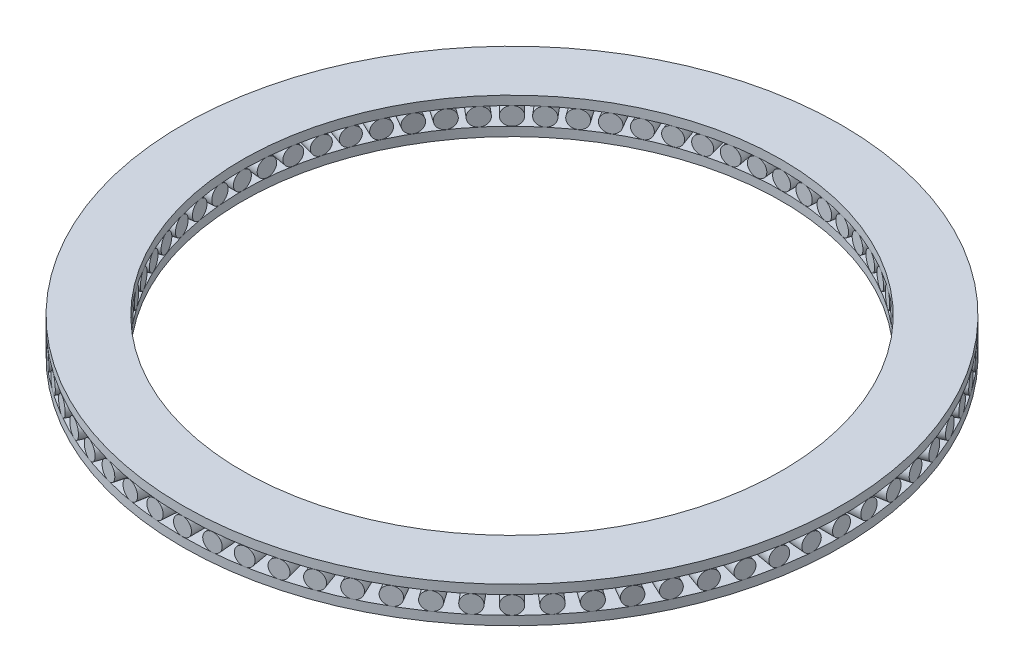
SolidWorks part; units mm, degrees
ref_plane "前视基准面" through (0, 0, 0) normal (0, 0, 1) x (1, 0, 0)
ref_plane "上视基准面" through (0, 0, 0) normal (0, 1, 0) x (1, 0, 0)
ref_plane "右视基准面" through (0, 0, 0) normal (1, 0, 0) x (0, 0, -1)
sketch "草图1" plane through (0, 0, 0) normal (0, 1, 0) x (1, 0, 0)
  circle A0 centre (0, 0) radius 55
  circle A1 centre (0, 0) radius 45
  dimension "D1" = 110
  dimension "D2" = 90
extrude "凸台-拉伸1" add sketch "草图1" along normal blind 1.5
sketch "草图2" plane through (0, 0, 0) normal (0, 0, 1) x (1, 0, 0)
  circle A0 centre (0, 3) radius 1.5
extrude "凸台-拉伸2" add sketch "草图2" along normal blind 10 from offset 45 separate body
pattern_circular "阵列(圆周)3" count 72 over 360 about axis through (0, 0, 0) along (0, 1, 0)
sketch "草图3" plane through (0, 0, 0) normal (0, -1, 0) x (1, 0, 0)
  circle A0 centre (0, 0) radius 55
  circle A1 centre (0, 0) radius 45
  dimension "D1" = 90
  dimension "D2" = 110
extrude "凸台-拉伸3" add sketch "草图3" against normal blind 1.5 from offset 4.5 separate body
